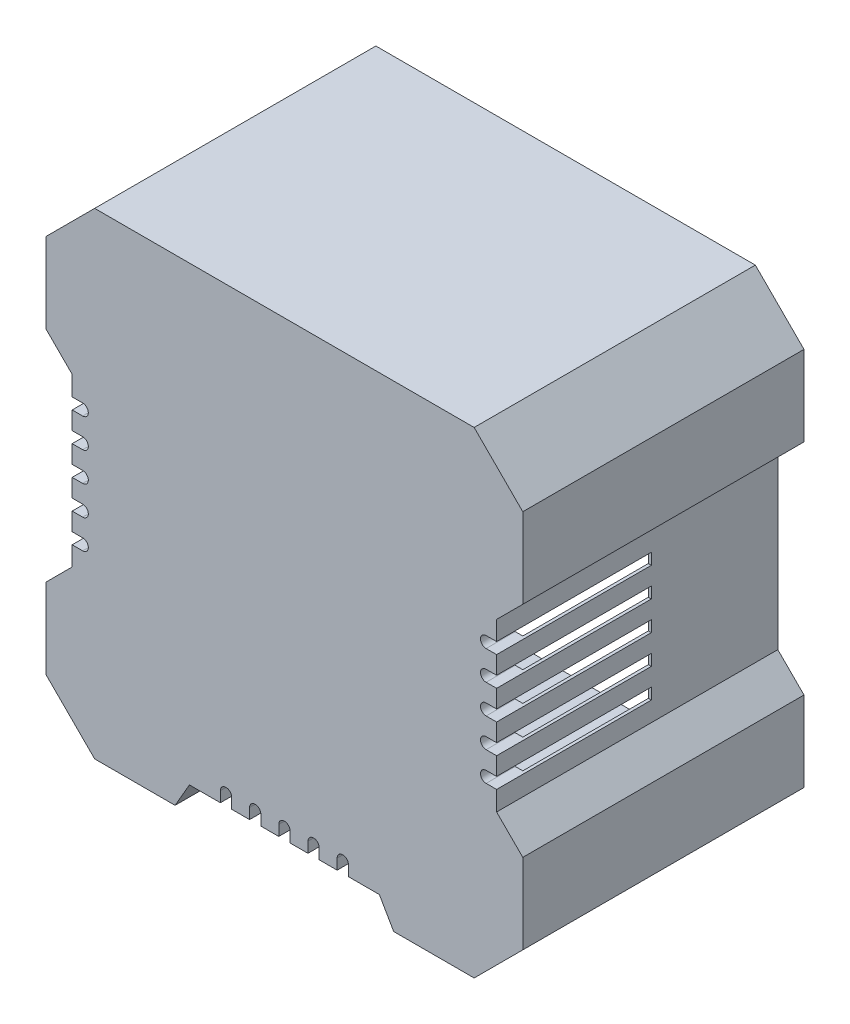
SolidWorks part; units mm, degrees
ref_plane "Front Plane" through (0, 0, 0) normal (0, 0, 1) x (1, 0, 0)
ref_plane "Top Plane" through (0, 0, 0) normal (0, 1, 0) x (1, 0, 0)
ref_plane "Right Plane" through (0, 0, 0) normal (1, 0, 0) x (0, 0, -1)
sketch "Sketch1" plane through (0, 0, 0) normal (0, 0, 1) x (1, 0, 0)
  line L1 (-24.5, -24.5) -> (24.5, -24.5)
  line L2 (-24.5, -24.5) -> (-24.5, 24.5)
  line L3 (-24.5, 24.5) -> (24.5, 24.5)
  line L4 (24.5, -24.5) -> (24.5, 24.5)
  line L5 (-24.5, -24.5) -> (24.5, 24.5) construction
  line L6 (-24.5, 24.5) -> (24.5, -24.5) construction
  point P0 (0, 0)
extrude "Boss-Extrude1" add sketch "Sketch1" along normal blind 28.9
sketch "Sketch2" plane through (0, 0, 0) normal (0, 0, -1) x (-1, 0, 0)
  line L0 (-24.5, -24.5) -> (-24.5, 24.5) construction
  line L1 (-21.5, -21.5) -> (21.5, -21.5)
  line L2 (-21.5, -21.5) -> (-21.5, 21.5)
  line L3 (-21.5, 21.5) -> (21.5, 21.5)
  line L4 (21.5, -21.5) -> (21.5, 21.5)
  line L5 (-21.5, -21.5) -> (21.5, 21.5) construction
  line L6 (-21.5, 21.5) -> (21.5, -21.5) construction
  line L8 (24.5, -24.5) -> (-24.5, -24.5) construction
  point P0 (0, 0)
  dimension "D1" = 3
  dimension "D2" = 3
extrude "Cut-Extrude1" cut sketch "Sketch2" against normal blind 25.9
sketch "Sketch3" plane through (0, 0, 28.9) normal (0, 0, 1) x (1, 0, 0)
  line L0 (730.5248, 394.173) -> (114.9496, 394.173) construction
  line L1 (-19.5, 24.5) -> (-24.5, 19.5)
  line L34 (-24.5, -19.5) -> (-19.5, -24.5)
  line L35 (19.5, -24.5) -> (24.5, -19.5)
  line L36 (24.5, 19.5) -> (19.5, 24.5)
  line L37 (24.5, -24.5) -> (24.5, 24.5)
  line L38 (24.5, 24.5) -> (-24.5, 24.5)
  line L39 (-24.5, 24.5) -> (-24.5, -24.5)
  line L40 (-24.5, -24.5) -> (24.5, -24.5)
  line L41 (24.5, -11.2615) -> (24.5, 11.2615)
  line L47 (-24.5, 11.2615) -> (-24.5, -11.2615)
  line L48 (-11.2341, -24.5) -> (11.2341, -24.5)
  line L49 (0, 0) -> (0, 41.5157) construction
  line L50 (24.5, 11.2615) -> (21.8094, 8.5709)
  line L51 (-24.5, -11.2615) -> (-21.8094, -8.5709)
  line L53 (-24.5, 11.2615) -> (-21.8094, 8.5709)
  line L54 (-21.8094, -8.5709) -> (-21.8094, 8.5709)
  line L55 (24.5, -11.2615) -> (21.8094, -8.5709)
  line L56 (21.8094, -8.5709) -> (21.8094, 8.5709)
  line L57 (-24.5, -24.5) -> (24.5, -24.5) construction
  line L58 (11.2341, -24.5) -> (9.7579, -21.9432)
  line L59 (9.7579, -21.9432) -> (-9.7579, -21.9432)
  line L60 (-9.7579, -21.9432) -> (-11.2341, -24.5)
  line L62 (-24.5, 24.5) -> (-19.5, 24.5)
  line L63 (-24.5, 24.5) -> (-24.5, 19.5)
  line L64 (-24.5, -24.5) -> (-19.5, -24.5)
  line L65 (24.5, 24.5) -> (24.5, 19.5)
  line L66 (-24.5, 24.5) -> (-22, 22) construction
  line L67 (-24.5, -24.5) -> (-22, -22) construction
  line L69 (24.5, -19.5) -> (24.5, -24.5)
  line L70 (22, -22) -> (24.5, -24.5) construction
  line L71 (19.5, -24.5) -> (24.5, -24.5)
  line L72 (-24.5, -19.5) -> (-24.5, -24.5)
  line L73 (22, 22) -> (24.5, 24.5) construction
  line L74 (-11.2341, -24.5) -> (11.2341, -24.5)
  line L75 (19.5, 24.5) -> (24.5, 24.5)
  line L76 (-24.5, 11.2615) -> (-24.5, -11.2615)
  line L77 (24.5, 11.2615) -> (24.5, -11.2615)
  point P15 (-24.5, 0)
  point P27 (0, -21.9432)
  point P35 (0, 0)
  line M37 (24.5, -24.5) -> (24.5, 24.5)
  line M38 (24.5, 24.5) -> (-24.5, 24.5)
  line M39 (-24.5, 24.5) -> (-24.5, -24.5)
  line M40 (-24.5, -24.5) -> (24.5, -24.5)
  dimension "D1" = 0
  dimension "D2" = 45
  dimension "D3" = 45
  dimension "D4" = 9.7579
  dimension "D9" = 120
extrude "Cut-Extrude2" cut sketch "Sketch3" against normal through all contours L51 L54 L53 M39 | L34 M39 M40 | L59 L60 L58 M40 | L35 M40 M37 | L56 L55 L50 M37 | L1 M38 M39 | L36 M37 M38
sketch "Sketch4" plane through (0, 0, 28.9) normal (0, 0, 1) x (1, 0, 0)
  line L16 (0, 0) -> (0, 33.5611) construction
  line L17 (0, 0) -> (-51.0352, 0) construction
  line L18 (-21.8094, -6.0177) -> (-20.7301, -6.0177) construction
  line L19 (-21.8094, -6.5966) -> (-20.7301, -6.5966)
  line L20 (-21.8094, -5.4388) -> (-20.7301, -5.4388)
  line L21 (-21.8094, -3.0177) -> (-20.7301, -3.0177) construction
  line L22 (-21.8094, -3.5966) -> (-20.7301, -3.5966)
  line L23 (-21.8094, -2.4388) -> (-20.7301, -2.4388)
  line L24 (-21.8094, -0.0177) -> (-20.7301, -0.0177) construction
  line L25 (-21.8094, -0.5966) -> (-20.7301, -0.5966)
  line L26 (-21.8094, 0.5612) -> (-20.7301, 0.5612)
  line L27 (-21.8094, 2.9823) -> (-20.7301, 2.9823) construction
  line L28 (-21.8094, 2.4034) -> (-20.7301, 2.4034)
  line L29 (-21.8094, 3.5612) -> (-20.7301, 3.5612)
  line L30 (-21.8094, 5.9823) -> (-20.7301, 5.9823) construction
  line L31 (-21.8094, 5.4034) -> (-20.7301, 5.4034)
  line L32 (-21.8094, 6.5612) -> (-20.7301, 6.5612)
  line L33 (21.8094, -5.9823) -> (20.7301, -5.9823) construction
  line L34 (21.8094, -5.4034) -> (20.7301, -5.4034)
  line L35 (21.8094, -6.5612) -> (20.7301, -6.5612)
  line L36 (21.8094, -2.9823) -> (20.7301, -2.9823) construction
  line L37 (21.8094, -2.4034) -> (20.7301, -2.4034)
  line L38 (21.8094, -3.5612) -> (20.7301, -3.5612)
  line L39 (21.8094, 0.0177) -> (20.7301, 0.0177) construction
  line L40 (21.8094, 0.5966) -> (20.7301, 0.5966)
  line L41 (21.8094, -0.5612) -> (20.7301, -0.5612)
  line L42 (21.8094, 3.0177) -> (20.7301, 3.0177) construction
  line L43 (21.8094, 3.5966) -> (20.7301, 3.5966)
  line L44 (21.8094, 2.4388) -> (20.7301, 2.4388)
  line L45 (21.8094, 6.0177) -> (20.7301, 6.0177) construction
  line L46 (21.8094, 6.5966) -> (20.7301, 6.5966)
  line L47 (21.8094, 5.4388) -> (20.7301, 5.4388)
  line L48 (6, -20.8639) -> (6, -21.9432) construction
  line L49 (5.4211, -20.8639) -> (5.4211, -21.9432)
  line L50 (6.5789, -20.8639) -> (6.5789, -21.9432)
  line L51 (3, -20.8639) -> (3, -21.9432) construction
  line L52 (2.4211, -20.8639) -> (2.4211, -21.9432)
  line L53 (3.5789, -20.8639) -> (3.5789, -21.9432)
  line L54 (0, -20.8639) -> (0, -21.9432) construction
  line L55 (-0.5789, -20.8639) -> (-0.5789, -21.9432)
  line L56 (0.5789, -20.8639) -> (0.5789, -21.9432)
  line L57 (-3, -20.8639) -> (-3, -21.9432) construction
  line L58 (-3.5789, -20.8639) -> (-3.5789, -21.9432)
  line L59 (-2.4211, -20.8639) -> (-2.4211, -21.9432)
  line L60 (-6, -20.8639) -> (-6, -21.9432) construction
  line L61 (-6.5789, -20.8639) -> (-6.5789, -21.9432)
  line L62 (-5.4211, -20.8639) -> (-5.4211, -21.9432)
  arc A10 (-21.8094, -6.5966) -> (-21.8094, -5.4388) centre (-21.8094, -6.0177) cw
  arc A11 (-20.7301, -5.4388) -> (-20.7301, -6.5966) centre (-20.7301, -6.0177) cw
  arc A12 (-21.8094, -3.5966) -> (-21.8094, -2.4388) centre (-21.8094, -3.0177) cw
  arc A13 (-20.7301, -2.4388) -> (-20.7301, -3.5966) centre (-20.7301, -3.0177) cw
  arc A14 (-21.8094, -0.5966) -> (-21.8094, 0.5612) centre (-21.8094, -0.0177) cw
  arc A15 (-20.7301, 0.5612) -> (-20.7301, -0.5966) centre (-20.7301, -0.0177) cw
  arc A16 (-21.8094, 2.4034) -> (-21.8094, 3.5612) centre (-21.8094, 2.9823) cw
  arc A17 (-20.7301, 3.5612) -> (-20.7301, 2.4034) centre (-20.7301, 2.9823) cw
  arc A18 (-21.8094, 5.4034) -> (-21.8094, 6.5612) centre (-21.8094, 5.9823) cw
  arc A19 (-20.7301, 6.5612) -> (-20.7301, 5.4034) centre (-20.7301, 5.9823) cw
  arc A20 (21.8094, -5.4034) -> (21.8094, -6.5612) centre (21.8094, -5.9823) cw
  arc A21 (20.7301, -6.5612) -> (20.7301, -5.4034) centre (20.7301, -5.9823) cw
  arc A22 (21.8094, -2.4034) -> (21.8094, -3.5612) centre (21.8094, -2.9823) cw
  arc A23 (20.7301, -3.5612) -> (20.7301, -2.4034) centre (20.7301, -2.9823) cw
  arc A24 (21.8094, 0.5966) -> (21.8094, -0.5612) centre (21.8094, 0.0177) cw
  arc A25 (20.7301, -0.5612) -> (20.7301, 0.5966) centre (20.7301, 0.0177) cw
  arc A26 (21.8094, 3.5966) -> (21.8094, 2.4388) centre (21.8094, 3.0177) cw
  arc A27 (20.7301, 2.4388) -> (20.7301, 3.5966) centre (20.7301, 3.0177) cw
  arc A28 (21.8094, 6.5966) -> (21.8094, 5.4388) centre (21.8094, 6.0177) cw
  arc A29 (20.7301, 5.4388) -> (20.7301, 6.5966) centre (20.7301, 6.0177) cw
  arc A30 (5.4211, -20.8639) -> (6.5789, -20.8639) centre (6, -20.8639) cw
  arc A31 (6.5789, -21.9432) -> (5.4211, -21.9432) centre (6, -21.9432) cw
  arc A32 (2.4211, -20.8639) -> (3.5789, -20.8639) centre (3, -20.8639) cw
  arc A33 (3.5789, -21.9432) -> (2.4211, -21.9432) centre (3, -21.9432) cw
  arc A34 (-0.5789, -20.8639) -> (0.5789, -20.8639) centre (0, -20.8639) cw
  arc A35 (0.5789, -21.9432) -> (-0.5789, -21.9432) centre (0, -21.9432) cw
  arc A36 (-3.5789, -20.8639) -> (-2.4211, -20.8639) centre (-3, -20.8639) cw
  arc A37 (-2.4211, -21.9432) -> (-3.5789, -21.9432) centre (-3, -21.9432) cw
  arc A38 (-6.5789, -20.8639) -> (-5.4211, -20.8639) centre (-6, -20.8639) cw
  arc A39 (-5.4211, -21.9432) -> (-6.5789, -21.9432) centre (-6, -21.9432) cw
  point P44 (-21.2698, -6.0177)
  point P51 (-21.2698, -3.0177)
  point P58 (-21.2698, -0.0177)
  point P65 (-21.2698, 2.9823)
  point P72 (-21.2698, 5.9823)
  point P78 (21.2698, -5.9823)
  point P85 (21.2698, -2.9823)
  point P92 (21.2698, 0.0177)
  point P99 (21.2698, 3.0177)
  point P106 (21.2698, 6.0177)
  point P117 (6, -21.4036)
  point P124 (3, -21.4036)
  point P131 (0, -21.4036)
  point P138 (-3, -21.4036)
  point P145 (-6, -21.4036)
extrude "Cut-Extrude3" cut sketch "Sketch4" against normal blind 15.9
